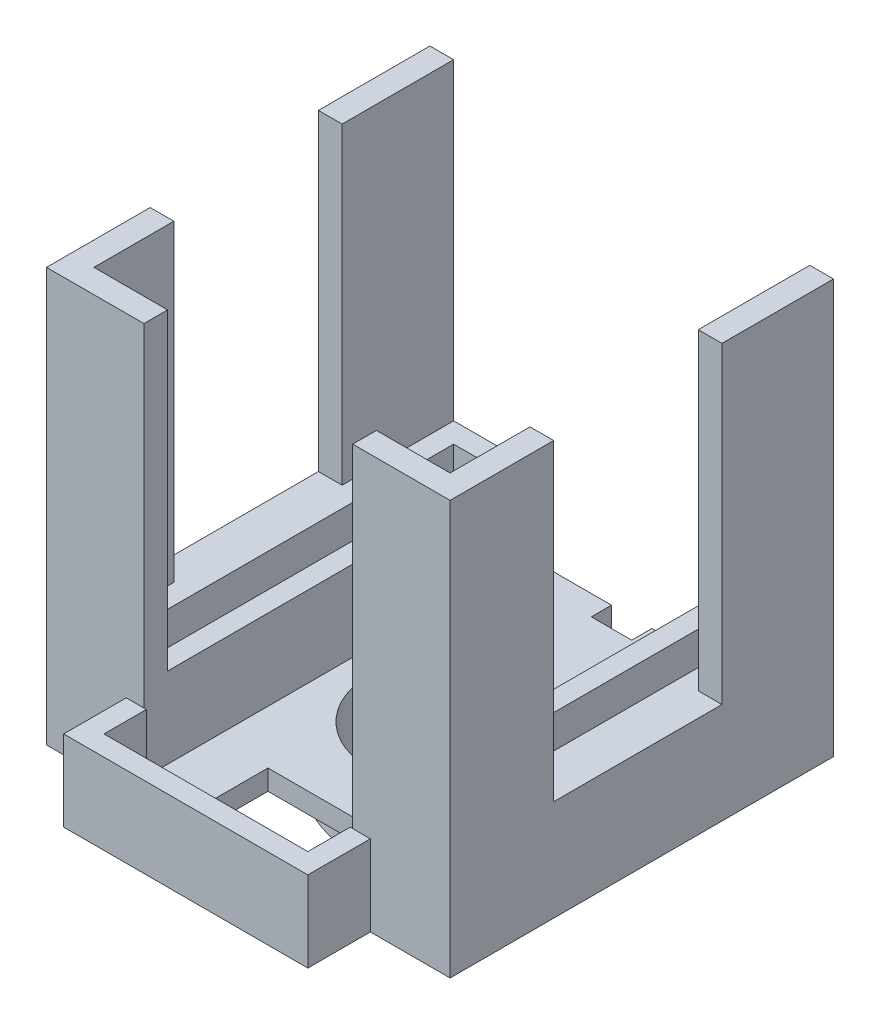
SolidWorks part; units mm, degrees
ref_plane "Front Plane" through (0, 0, 0) normal (0, 0, 1) x (1, 0, 0)
ref_plane "Top Plane" through (0, 0, 0) normal (0, 1, 0) x (1, 0, 0)
ref_plane "Right Plane" through (0, 0, 0) normal (1, 0, 0) x (0, 0, -1)
sketch "Sketch1" plane through (0, 0, 0) normal (0, 1, 0) x (1, 0, 0)
  line L1 (40, -2) -> (40, -40)
  line L2 (40, -40) -> (0, -40)
  line L4 (0, -2) -> (0, -40)
  line L7 (2.35, -20) -> (2.35, -2.35)
  line L9 (37.65, -2.35) -> (37.65, -20)
  line L10 (37.65, -20) -> (37.65, -37.65)
  line L11 (37.65, -37.65) -> (2.35, -37.65)
  line L12 (2.35, -37.65) -> (2.35, -20)
  line L18 (2.35, -2) -> (0, -2)
  line L19 (2.35, -2) -> (2.35, -2.35)
  line L20 (37.65, -2) -> (37.65, -2.35)
  line L21 (37.65, -2) -> (40, -2)
extrude "Boss-Extrude2" add sketch "Sketch1" along normal blind 28
sketch "Sketch3" plane through (0, 0, 0) normal (0, -1, 0) x (1, 0, 0)
  line L1 (0, 40) -> (40, 40)
  line L2 (0, 40) -> (0, 2)
  line L3 (0, 2) -> (40, 2)
  line L4 (40, 40) -> (40, 2)
extrude "Boss-Extrude3" add sketch "Sketch3" along normal blind 10
sketch "Sketch5" plane through (0, 0, 0) normal (0, 1, 0) x (1, 0, 0)
  line L0 (9.65, -20) -> (9.65, -57.9)
  line L1 (2.35, -2) -> (37.65, -2) construction
  line L2 (9.65, -2) -> (30.35, -2)
  line L5 (30.35, -20) -> (30.35, -2)
  line L6 (9.65, -2) -> (9.65, -20)
  line L7 (9.65, -57.9) -> (20, -57.9)
  line L8 (20, -57.9) -> (30.35, -57.9)
  line L9 (30.35, -57.9) -> (30.35, -20)
extrude "Cut-Extrude2" cut sketch "Sketch5" against normal blind 8
sketch "Sketch6" plane through (0, -8, 0) normal (0, 1, 0) x (1, 0, 0)
  line L1 (9.65, -2) -> (30.35, -2)
  line L2 (9.65, -2) -> (9.65, -40)
  line L3 (9.65, -40) -> (30.35, -40)
  line L4 (30.35, -2) -> (30.35, -40)
extrude "Cut-Extrude3" cut sketch "Sketch6" along normal blind 43
sketch "Sketch7" plane through (0, -8, 0) normal (0, 1, 0) x (1, 0, 0)
  line L1 (30.35, -2) -> (9.65, -2) construction
  line L2 (20, -4) -> (18, -4)
  line L3 (18, -4) -> (18, -2)
  line L4 (18, -2) -> (22, -2)
  line L5 (22, -2) -> (22, -4)
  line L6 (22, -4) -> (20, -4)
extrude "Cut-Extrude4" cut sketch "Sketch7" against normal blind 43
sketch "Sketch9" plane through (0, -10, 0) normal (0, -1, 0) x (1, 0, 0)
  line L4 (30.1, 44.2) -> (30.1, 40)
  line L5 (40, 40) -> (0, 40) construction
  line L6 (9.9, 44.2) -> (9.9, 40)
  line L8 (32.1, 46.2) -> (32.1, 40)
  line L10 (7.9, 46.2) -> (7.9, 40)
  line L13 (18, 46.2) -> (9.9, 46.2)
  line L14 (7.9, 40) -> (9.9, 40)
  line L15 (7.9, 38) -> (32.1, 38) construction
  line L16 (7.9, 58.3) -> (7.9, 38) construction
  line L17 (32.1, 58.3) -> (32.1, 38) construction
  line L18 (30.1, 40) -> (32.1, 40)
  line L19 (9.9, 46.2) -> (7.9, 46.2)
  line L20 (9.9, 40) -> (30.1, 40) construction
  line L21 (18, 46.2) -> (32.1, 46.2)
  line L23 (9.9, 56.3) -> (9.9, 40) construction
  line L24 (20, 56.3) -> (9.9, 56.3) construction
  line L25 (20, 58.3) -> (7.9, 58.3) construction
  line L26 (20, 56.3) -> (30.1, 56.3) construction
  line L27 (20, 58.3) -> (32.1, 58.3) construction
  line L28 (30.1, 56.3) -> (30.1, 40) construction
  line L29 (9.9, 44.2) -> (30.1, 44.2)
extrude "Boss-Extrude5" add sketch "Sketch9" against normal blind 8
sketch "Sketch10" plane through (0, -10, 0) normal (0, -1, 0) x (1, 0, 0)
  circle A0 centre (20, 20) radius 10
extrude "Boss-Extrude6" add sketch "Sketch10" along normal blind 4
sketch "Sketch11" plane through (0, -14, 0) normal (0, -1, 0) x (-1, 0, 0)
  circle A0 centre (-20, -20) radius 8
extrude "Cut-Extrude5" cut sketch "Sketch11" against normal blind 4
sketch "Sketch12" plane through (0, -10, 0) normal (0, -1, 0) x (1, 0, 0)
  circle A0 centre (20, 20) radius 8
extrude "Cut-Extrude6" cut sketch "Sketch12" against normal blind 10
sketch "Sketch13" plane through (0, 0, 0) normal (0, 1, 0) x (1, 0, 0)
  line L0 (4.35, -35.65) -> (4.35, -4)
  line L5 (4.35, -4) -> (7.65, -4)
  line L6 (7.65, -35.65) -> (7.65, -4)
  line L7 (4.35, -35.65) -> (7.65, -35.65)
extrude "Cut-Extrude7" cut sketch "Sketch13" against normal blind 10
sketch "Sketch14" plane through (0, 0, 0) normal (0, 1, 0) x (1, 0, 0)
  line L0 (32.35, -35.65) -> (32.35, -4)
  line L5 (32.35, -4) -> (35.65, -4)
  line L6 (35.65, -35.65) -> (35.65, -4)
  line L7 (32.35, -35.65) -> (35.65, -35.65)
extrude "Cut-Extrude8" cut sketch "Sketch14" against normal blind 10
sketch "Sketch15" plane through (40, 0, 0) normal (1, 0, 0) x (0, 0, -1)
  line L0 (-40, 28) -> (-2, 28) construction
  line L1 (-29.7328, 28) -> (-13.0529, 28)
  line L2 (-29.7328, 28) -> (-29.7328, 0)
  line L3 (-29.7328, 0) -> (-13.0529, 0)
  line L4 (-13.0529, 28) -> (-13.0529, 0)
extrude "Cut-Extrude9" cut sketch "Sketch15" against normal blind 253
sketch "Sketch16" plane through (0, -10, 0) normal (0, -1, 0) x (1, 0, 0)
  line L2 (14.95, 33) -> (25.05, 33)
  line L4 (14.95, 40) -> (25.05, 40)
  line L6 (14.95, 33) -> (14.95, 40)
  line L7 (25.05, 40) -> (25.05, 33)
extrude "Cut-Extrude11" cut sketch "Sketch16" against normal blind 13
sketch "Sketch17" plane through (0, 28, 0) normal (0, 1, 0) x (1, 0, 0)
  line L0 (40, -40) -> (40, -29.7328)
  line L1 (40, -29.7328) -> (37.65, -29.7328)
  line L2 (37.65, -29.7328) -> (37.65, -37.65)
  line L3 (37.65, -37.65) -> (30.35, -37.65)
  line L4 (30.35, -37.65) -> (30.35, -40)
  line L5 (30.35, -40) -> (40, -40)
  line L6 (9.65, -40) -> (0, -40)
  line L7 (0, -40) -> (0, -29.7328)
  line L8 (0, -29.7328) -> (0, -40) construction
  line L9 (0, -29.7328) -> (2.35, -29.7328)
  line L10 (2.35, -29.7328) -> (2.35, -37.65)
  line L11 (2.35, -37.65) -> (9.65, -37.65)
  line L12 (9.65, -37.65) -> (2.35, -37.65) construction
  line L13 (9.65, -40) -> (9.65, -37.65) construction
  line L14 (9.65, -37.65) -> (9.65, -40)
  line L15 (2.35, -13.0529) -> (2.35, -2)
  line L16 (2.35, -2) -> (0, -2)
  line L17 (0, -2) -> (0, -13.0529)
  line L18 (0, -13.0529) -> (2.35, -13.0529)
  line L19 (40, -2) -> (40, -13.0529)
  line L20 (40, -13.0529) -> (37.65, -13.0529)
  line L21 (37.65, -13.0529) -> (37.65, -2)
  line L22 (37.65, -2) -> (40, -2)
extrude "Boss-Extrude7" add sketch "Sketch17" along normal blind 3
